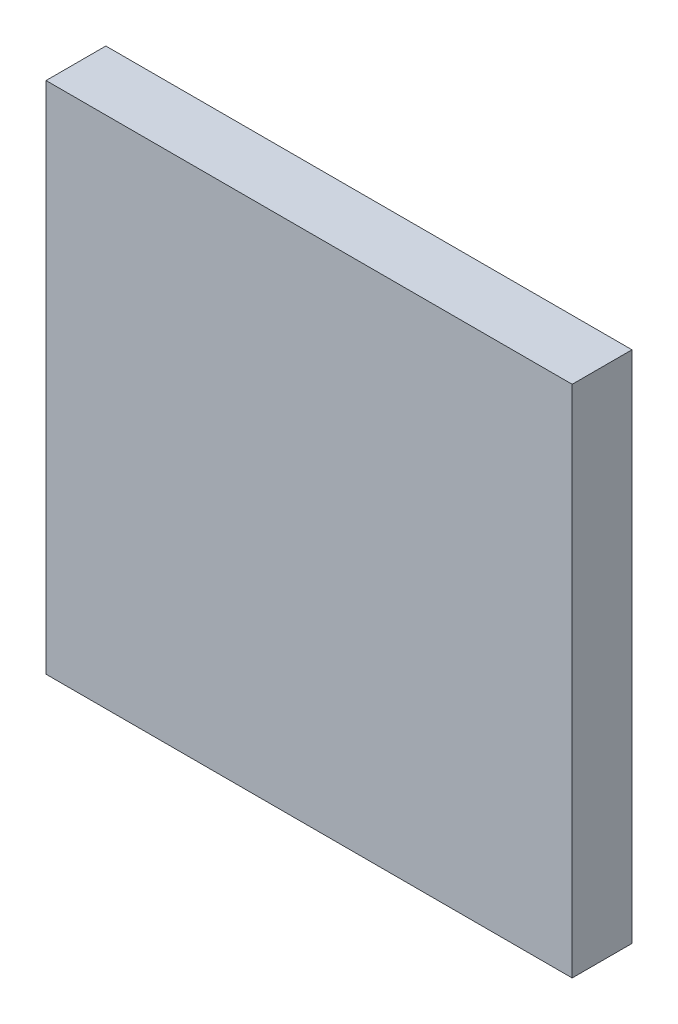
SolidWorks part; units mm, degrees
ref_plane "Front Plane" through (0, 0, 0) normal (0, 0, 1) x (1, 0, 0)
ref_plane "Top Plane" through (0, 0, 0) normal (0, 1, 0) x (1, 0, 0)
ref_plane "Right Plane" through (0, 0, 0) normal (1, 0, 0) x (0, 0, -1)
sketch "Sketch1" plane through (0, 0, 0) normal (0, 0, 1) x (1, 0, 0)
  line L1 (0, 0) -> (88, 0)
  line L2 (0, 0) -> (0, 86)
  line L3 (0, 86) -> (88, 86)
  line L4 (88, 0) -> (88, 86)
  dimension "D1" = 88
  dimension "D2" = 86
extrude "Boss-Extrude1" add sketch "Sketch1" along normal blind 10
